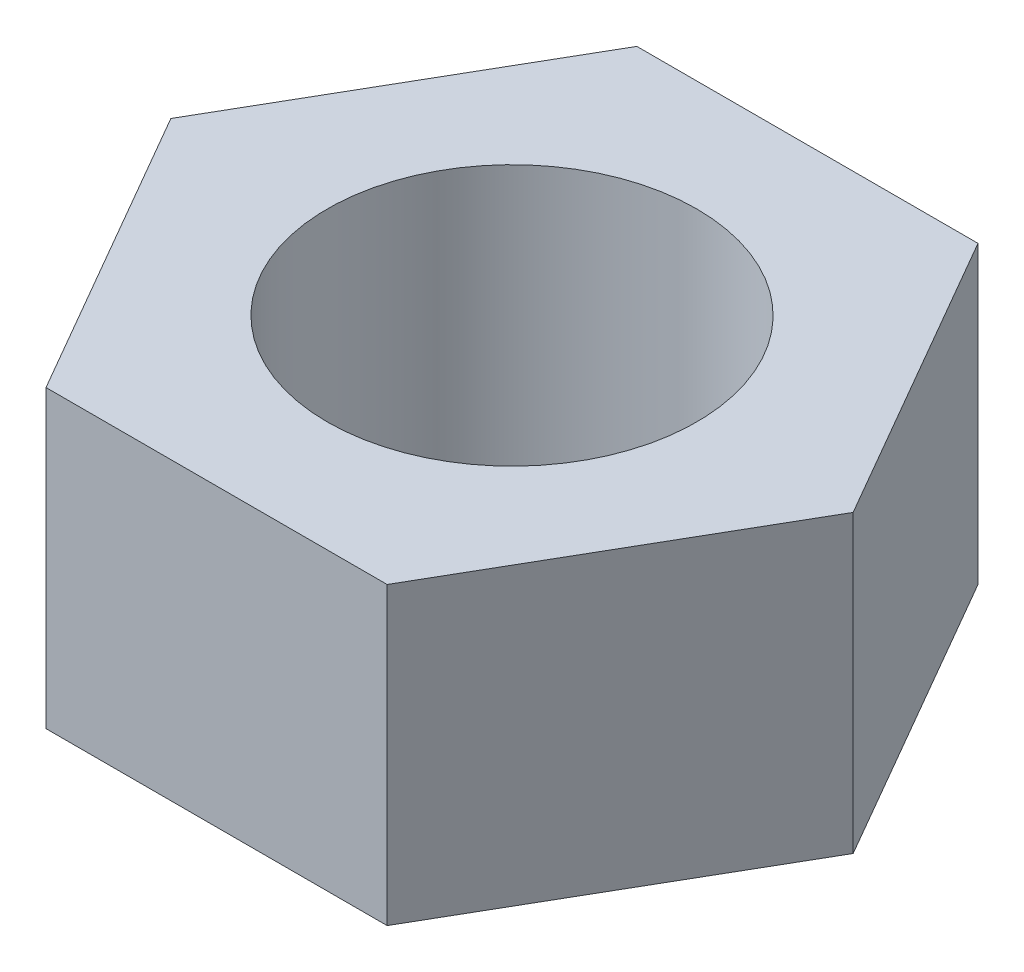
SolidWorks part; units mm, degrees
ref_plane "Front Plane" through (0, 0, 0) normal (0, 0, 1) x (1, 0, 0)
ref_plane "Top Plane" through (0, 0, 0) normal (0, 1, 0) x (1, 0, 0)
ref_plane "Right Plane" through (0, 0, 0) normal (1, 0, 0) x (0, 0, -1)
sketch "Sketch1" plane through (0, 0, 0) normal (0, 1, 0) x (1, 0, 0)
  line L0 (0, 4) -> (0, -4) construction
  line L1 (-2.3094, -4) -> (2.3094, -4)
  line L2 (-2.3094, 4) -> (2.3094, 4)
  line L3 (-3.4641, -2) -> (3.4641, 2) construction
  line L4 (4.6188, 0) -> (2.3094, 4)
  line L5 (-2.3094, -4) -> (-4.6188, 0)
  line L6 (3.4641, -2) -> (-3.4641, 2) construction
  line L7 (-2.3094, 4) -> (-4.6188, 0)
  line L8 (4.6188, 0) -> (2.3094, -4)
  circle A0 centre (0, 0) radius 2.5
  point P4 (0, 0)
  point P8 (0, -4)
  point P11 (0, 4)
  point P25 (0, 0)
  dimension "D3" = 5
  dimension "D1" = 8
  dimension "D2" = 3
extrude "Boss-Extrude1" add sketch "Sketch1" along normal blind 4
